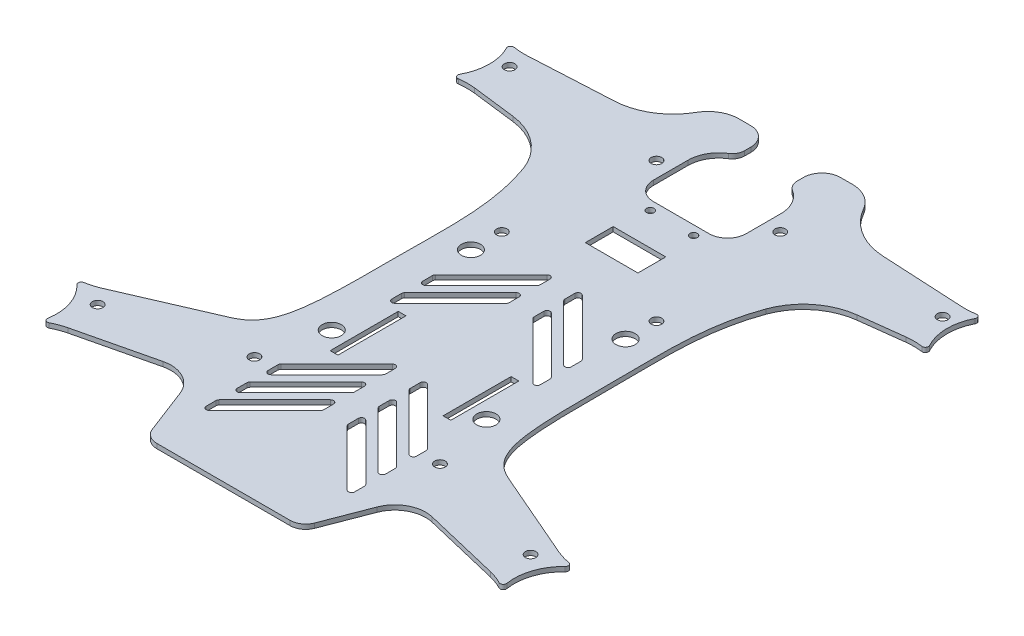
SolidWorks part; units mm, degrees
ref_plane "Front Plane" through (0, 0, 0) normal (0, 0, 1) x (1, 0, 0)
ref_plane "Top Plane" through (0, 0, 0) normal (0, 1, 0) x (1, 0, 0)
ref_plane "Right Plane" through (0, 0, 0) normal (1, 0, 0) x (0, 0, -1)
sketch "Sketch1" plane through (0, 0, 0) normal (0, 1, 0) x (1, 0, 0)
  line L1 (0, 0) -> (0, -50000) construction
  line L12 (-31.8558, -72.1926) -> (-26.2334, -86.7965)
  line L13 (-21.5672, -90) -> (21.5672, -90)
  line L14 (26.2334, -86.7965) -> (31.8558, -72.1926)
  line L15 (43.5115, -66.0592) -> (68.2422, -71.9668)
  line L16 (73.7738, -55.3719) -> (45, -42.8995)
  line L17 (55.6344, 59.1911) -> (69.7041, 60.9187)
  line L18 (70.267, 78.432) -> (43.3651, 79.8419)
  line L19 (18.3249, 95) -> (-18.3249, 95)
  line L20 (-43.3651, 79.8419) -> (-70.267, 78.432)
  line L21 (-69.7041, 60.9187) -> (-55.6344, 59.1911)
  line L22 (-45, -42.8995) -> (-73.7738, -55.3719)
  line L23 (-68.2422, -71.9668) -> (-43.5115, -66.0592)
  line L24 (-31.8558, -72.1926) -> (-26.2334, -86.7965)
  line L25 (-21.5672, -90) -> (21.5672, -90)
  line L26 (26.2334, -86.7965) -> (31.8558, -72.1926)
  line L27 (43.5115, -66.0592) -> (68.2422, -71.9668)
  line L28 (73.7738, -55.3719) -> (45, -42.8995)
  line L29 (55.6344, 59.1911) -> (69.7041, 60.9187)
  line L30 (70.267, 78.432) -> (43.3651, 79.8419)
  line L31 (18.3249, 95) -> (-18.3249, 95)
  line L32 (-43.3651, 79.8419) -> (-70.267, 78.432)
  line L33 (-69.7041, 60.9187) -> (-55.6344, 59.1911)
  line L34 (-45, -42.8995) -> (-73.7738, -55.3719)
  line L35 (-68.2422, -71.9668) -> (-43.5115, -66.0592)
  arc A2 (-18.3249, 95) -> (-27.0205, 89.9382) centre (-18.3249, 85) ccw construction
  arc A3 (-18.3249, 95) -> (-27.0205, 89.9382) centre (-18.3249, 85) ccw
  arc A22 (21.5672, -90) -> (26.2334, -86.7965) centre (21.5672, -85) ccw
  arc A23 (21.5672, -90) -> (26.2334, -86.7965) centre (21.5672, -85) ccw
  arc A24 (43.5115, -66.0592) -> (31.8558, -72.1926) centre (41.1881, -75.7855) ccw
  arc A25 (79.1275, -78.8198) -> (68.2422, -71.9668) centre (63.5953, -91.4195) ccw
  arc A26 (79.1275, -78.8198) -> (86.5939, -56.4207) centre (90, -70) ccw
  arc A27 (73.7738, -55.3719) -> (86.5939, -56.4207) centre (81.728, -37.0216) ccw
  arc A28 (55.6344, 59.1911) -> (39.2597, 46.1303) centre (58.0718, 39.3402) ccw
  arc A29 (82.6465, 58.0867) -> (69.7041, 60.9187) centre (72.1415, 41.0677) ccw
  arc A30 (82.6465, 58.0867) -> (82.3057, 81.696) centre (90, 70) ccw
  arc A31 (70.267, 78.432) -> (82.3057, 81.696) centre (71.3137, 98.4046) ccw
  arc A32 (27.0205, 89.9382) -> (43.3651, 79.8419) centre (44.4119, 99.8145) ccw
  arc A33 (27.0205, 89.9382) -> (18.3249, 95) centre (18.3249, 85) ccw
  arc A34 (-18.3249, 95) -> (-27.0205, 89.9382) centre (-18.3249, 85) ccw
  arc A35 (-43.3651, 79.8419) -> (-27.0205, 89.9382) centre (-44.4119, 99.8145) ccw
  arc A36 (-82.3057, 81.696) -> (-70.267, 78.432) centre (-71.3137, 98.4046) ccw
  arc A37 (-82.3057, 81.696) -> (-82.6465, 58.0867) centre (-90, 70) ccw
  arc A38 (-69.7041, 60.9187) -> (-82.6465, 58.0867) centre (-72.1415, 41.0677) ccw
  arc A39 (-39.2597, 46.1303) -> (-55.6344, 59.1911) centre (-58.0718, 39.3402) ccw
  arc A40 (-86.5939, -56.4207) -> (-73.7738, -55.3719) centre (-81.728, -37.0216) ccw
  arc A41 (-86.5939, -56.4207) -> (-79.1275, -78.8198) centre (-90, -70) ccw
  arc A42 (-68.2422, -71.9668) -> (-79.1275, -78.8198) centre (-63.5953, -91.4195) ccw
  arc A43 (-31.8558, -72.1926) -> (-43.5115, -66.0592) centre (-41.1881, -75.7855) ccw
  arc A44 (-26.2334, -86.7965) -> (-21.5672, -90) centre (-21.5672, -85) ccw
  arc A45 (-26.2334, -86.7965) -> (-21.5672, -90) centre (-21.5672, -85) ccw
  arc A46 (43.5115, -66.0592) -> (31.8558, -72.1926) centre (41.1881, -75.7855) ccw
  arc A47 (68.2422, -71.9668) -> (74.7411, -74.8131) centre (63.5953, -91.4195) cw
  arc A49 (74.7411, -74.8131) -> (80.6807, -56.9942) centre (90, -70) cw
  arc A50 (55.6344, 59.1911) -> (39.2597, 46.1303) centre (58.0718, 39.3402) ccw
  arc A51 (80.6807, -56.9942) -> (73.7738, -55.3719) centre (81.728, -37.0216) cw
  arc A53 (69.7041, 60.9187) -> (77.1837, 60.4217) centre (72.1415, 41.0677) cw
  arc A54 (27.0205, 89.9382) -> (43.3651, 79.8419) centre (44.4119, 99.8145) ccw
  arc A55 (27.0205, 89.9382) -> (18.3249, 95) centre (18.3249, 85) ccw
  arc A57 (-43.3651, 79.8419) -> (-27.0205, 89.9382) centre (-44.4119, 99.8145) ccw
  arc A58 (-76.9126, 79.2043) -> (-70.267, 78.432) centre (-71.3137, 98.4046) ccw
  arc A60 (-69.7041, 60.9187) -> (-77.1837, 60.4217) centre (-72.1415, 41.0677) ccw
  arc A61 (-39.2597, 46.1303) -> (-55.6344, 59.1911) centre (-58.0718, 39.3402) ccw
  arc A62 (-80.6807, -56.9942) -> (-73.7738, -55.3719) centre (-81.728, -37.0216) ccw
  arc A64 (-68.2422, -71.9668) -> (-74.7411, -74.8131) centre (-63.5953, -91.4195) ccw
  arc A65 (-31.8558, -72.1926) -> (-43.5115, -66.0592) centre (-41.1881, -75.7855) ccw
  arc A131 (-77.1837, 60.4217) -> (-76.9126, 79.2043) centre (-90, 70) ccw
  arc A133 (-82.3057, 81.696) -> (-70.267, 78.432) centre (-71.3137, 98.4046) ccw construction
  arc A134 (-74.7411, -74.8131) -> (-80.6807, -56.9942) centre (-90, -70) ccw
  arc A135 (-68.2422, -71.9668) -> (-79.1275, -78.8198) centre (-63.5953, -91.4195) ccw construction
  arc A136 (77.1837, 60.4217) -> (76.9126, 79.2043) centre (90, 70) cw
  arc A137 (76.9126, 79.2043) -> (70.267, 78.432) centre (71.3137, 98.4046) cw
  spline S2 degree 3 poles (1694.5385, -1156.2791) (84.776, 273.5101) (33.8756, -163.1642) (35.6323, 88.6713) (8.3125, 229.0595) (2032.4445, 110.5715) knots -2.898173 -2.898173 -2.898173 -2.898173 0.549242 0.649242 2.552813 2.552813 2.552813 2.552813 only from (45, -42.8995) to (39.2597, 46.1303)
  spline S3 degree 3 poles (-2032.3973, 110.5742) (-8.3129, 229.0574) (-35.6323, 88.6706) (-33.8756, -163.1654) (-84.7767, 273.5164) (-1694.5744, -1156.311) knots -1.552799 -1.552799 -1.552799 -1.552799 0.350758 0.450758 3.898198 3.898198 3.898198 3.898198 only from (-39.2597, 46.1303) to (-45, -42.8995)
  spline S4 degree 3 poles (45, -42.8995) (36.3436, -39.1473) (34.8096, -29.2686) (35.1069, 13.3566) (34.256, 32.2676) (39.2597, 46.1303) knots 0 0 0 0 0.549242 0.649242 0.922623 0.922623 0.922623 0.922623
  spline S5 degree 3 poles (-39.2597, 46.1303) (-34.256, 32.2676) (-35.1069, 13.3566) (-34.8096, -29.2686) (-36.3436, -39.1473) (-45, -42.8995) knots 0.077377 0.077377 0.077377 0.077377 0.350758 0.450758 1 1 1 1
  dimension "D4" = 32
  dimension "D1" = 0
extrude "Boss-Extrude1" add sketch "Sketch1" along normal blind 1.5
sketch "Sketch2" plane through (0, 1.5, 0) normal (0, 1, 0) x (1, 0, 0)
  circle A0 centre (-70, 72.5) radius 1.7 construction
  circle A1 centre (-70, 72.5) radius 1.7
  circle A2 centre (-20, 70) radius 1.7 construction
  circle A3 centre (-20, 70) radius 1.7
  circle A4 centre (20, 70) radius 1.7 construction
  circle A5 centre (20, 70) radius 1.7
  circle A6 centre (70, 72.5) radius 1.7 construction
  circle A7 centre (70, 72.5) radius 1.7
  circle A8 centre (30, -50) radius 1.7 construction
  circle A9 centre (30, -50) radius 1.7
  circle A10 centre (70, -60.6981) radius 1.7 construction
  circle A11 centre (70, -60.6981) radius 1.7
  circle A12 centre (-30, -50) radius 1.7 construction
  circle A13 centre (-30, -50) radius 1.7
  circle A14 centre (-70, -60.6981) radius 1.7 construction
  circle A15 centre (-70, -60.6981) radius 1.7
  circle A16 centre (-25, 25) radius 1.7 construction
  circle A17 centre (-25, 25) radius 1.7
  circle A18 centre (25, 25) radius 1.7 construction
  circle A19 centre (25, 25) radius 1.7
extrude "Cut-Extrude1" cut sketch "Sketch2" against normal through all
sketch "Sketch3" plane through (0, 1.5, 0) normal (0, 1, 0) x (1, 0, 0)
  line L0 (0, 0) -> (0, -50000) construction
  line L1 (-8.5, 83) -> (-15, 83)
  line L2 (15, 83) -> (8.5, 83)
  line L3 (15, 83) -> (15, 58)
  line L4 (15, 58) -> (-15, 58)
  line L5 (-15, 83) -> (-15, 58)
  line L6 (15, 83) -> (-15, 58) construction
  line L7 (15, 58) -> (-15, 83) construction
  line L8 (-8.5, 83) -> (-8.5, 95)
  line L9 (18.3249, 95) -> (-18.3249, 95) construction
  line L10 (-8.5, 95) -> (8.5, 95)
  line L11 (8.5, 95) -> (8.5, 83)
  circle A0 centre (-7, 55) radius 1.2
  circle A1 centre (7, 55) radius 1.2
  point P3 (0, 70.5)
  dimension "D4" = 17
  dimension "D5" = 14
  dimension "D6" = 2.4
  dimension "D1" = 25
  dimension "D2" = 58
  dimension "D3" = 30
  dimension "D7" = 3
extrude "Cut-Extrude2" cut sketch "Sketch3" against normal through all
fillet "Fillet1" radius 6 2 edges at (8.5, 0.75, -95) (-8.5, 0.75, -95)
fillet "Fillet2" radius 4 2 edges at (8.5, 0.75, -83) (-8.5, 0.75, -83)
fillet "Fillet3" radius 10 2 edges at (15, 0.75, -83) (-15, 0.75, -83)
fillet "Fillet4" radius 6 2 edges at (15, 0.75, -58) (-15, 0.75, -58)
sketch "Sketch4" plane through (0, 1.5, 0) normal (0, 1, 0) x (1, 0, 0)
  line L0 (0, 0) -> (0, -50000) construction
  circle A0 centre (-25, 15) radius 3.1
  circle A1 centre (25, 15) radius 3.1
  circle A2 centre (-25, -30) radius 3.1
  circle A3 centre (25, -30) radius 3.1
  dimension "D1" = 6.2
  dimension "D2" = 50
  dimension "D3" = 45
  dimension "D4" = 15
extrude "Cut-Extrude3" cut sketch "Sketch4" against normal through all
sketch "Sketch5" plane through (0, 1.5, 0) normal (0, 1, 0) x (1, 0, 0)
  line L1 (8.5, 44.5) -> (-8.5, 44.5)
  line L2 (8.5, 44.5) -> (8.5, 35.5)
  line L3 (8.5, 35.5) -> (-8.5, 35.5)
  line L4 (-8.5, 44.5) -> (-8.5, 35.5)
  line L5 (8.5, 44.5) -> (-8.5, 35.5) construction
  line L6 (8.5, 35.5) -> (-8.5, 44.5) construction
  point P0 (0, 40)
  dimension "D1" = 17
  dimension "D2" = 9
  dimension "D3" = 40
extrude "Cut-Extrude4" cut sketch "Sketch5" against normal through all
sketch "Sketch6" plane through (0, 1.5, 0) normal (0, 1, 0) x (1, 0, 0)
  line L0 (-24, -8) -> (-4, 12) [skipped]
  line L1 (-4, 22) -> (-4, 16)
  line L2 (-4, 16) -> (-24, -4)
  line L3 (-24, -4) -> (-24, 2)
  line L4 (-24, 2) -> (-4, 22)
  line L5 (-4, 12) -> (-4, 6)
  line L6 (-24, -8) -> (-4, 12)
  line L7 (-24, -14) -> (-24, -8)
  line L8 (-4, 6) -> (-24, -14)
  line L9 (-24, -48) -> (-4, -28)
  line L10 (-24, -54) -> (-24, -48)
  line L11 (-4, -34) -> (-24, -54)
  line L12 (-4, -28) -> (-4, -34)
  line L13 (-24, -14) -> (-24, -8) [skipped]
  line L14 (-4, 6) -> (-24, -14) [skipped]
  line L15 (-4, 12) -> (-4, 6) [skipped]
  line L16 (-24, -18) -> (-4, 2) [skipped]
  line L17 (-24, -24) -> (-24, -18) [skipped]
  line L18 (-4, -4) -> (-24, -24) [skipped]
  line L19 (-4, 2) -> (-4, -4) [skipped]
  line L20 (-24, -28) -> (-4, -8) [skipped]
  line L21 (-24, -34) -> (-24, -28) [skipped]
  line L22 (-4, -14) -> (-24, -34) [skipped]
  line L23 (-4, -8) -> (-4, -14) [skipped]
  line L24 (-24, -38) -> (-4, -18) [skipped]
  line L25 (-24, -44) -> (-24, -38) [skipped]
  line L26 (-4, -24) -> (-24, -44) [skipped]
  line L27 (-4, -18) -> (-4, -24) [skipped]
  line L32 (-24, -58) -> (-4, -38)
  line L33 (-24, -64) -> (-24, -58)
  line L34 (-4, -44) -> (-24, -64)
  line L35 (-4, -38) -> (-4, -44)
  line L36 (-24, -68) -> (-4, -48)
  line L37 (-24, -74) -> (-24, -68)
  line L38 (-4, -54) -> (-24, -74)
  line L39 (-4, -48) -> (-4, -54)
  line L95 (-24, -48) -> (-4, -28) [skipped]
  line L96 (-4, -28) -> (-4, -34) [skipped]
  line L97 (-4, -34) -> (-24, -54) [skipped]
  line L98 (-24, -54) -> (-24, -48) [skipped]
  line L99 (-24, -18) -> (-4, 2) [skipped]
  line L100 (-24, -24) -> (-24, -18) [skipped]
  line L101 (-4, -4) -> (-24, -24) [skipped]
  line L102 (-4, 2) -> (-4, -4) [skipped]
  dimension "D1" = 20
  dimension "D2" = 8
  dimension "D3" = 22
  dimension "D4" = 20
  dimension "D5" = 6
  dimension "D6" = 3
  dimension "D7" = 2
  dimension "D8" = 4
extrude "Cut-Extrude5" cut sketch "Sketch6" against normal through all
fillet "Fillet5" radius 1 20 edges at (-24, 0.75, 14) (-24, 0.75, 8) (-4, 0.75, -6) (-4, 0.75, -12) (-4, 0.75, -16) (-4, 0.75, -22) (-24, 0.75, 4) (-24, 0.75, -2) (-4, 0.75, 38) (-4, 0.75, 44) (-4, 0.75, 48) (-4, 0.75, 54) (-24, 0.75, 74) (-24, 0.75, 68) (-24, 0.75, 64) (-24, 0.75, 58) (-4, 0.75, 28) (-4, 0.75, 34) (-24, 0.75, 54) (-24, 0.75, 48)
mirror "Mirror1" about plane through (0, 0, 0) normal (1, 0, 0) of "Fillet5", "Cut-Extrude5"
fillet "Fillet6" radius 1 8 edges at (77.1837, 0.75, -60.4217) (76.9126, 0.75, -79.2043) (74.7411, 0.75, 74.8131) (80.6807, 0.75, 56.9942) (-74.7411, 0.75, 74.8131) (-80.6807, 0.75, 56.9942) (-77.1837, 0.75, -60.4217) (-76.9126, 0.75, -79.2043)
sketch "Sketch7" plane through (0, 1.5, 0) normal (0, 1, 0) x (1, 0, 0)
  line L0 (0, 0) -> (0, -50000) construction
  line L1 (17, -14) -> (17, -36)
  line L2 (-19.5, -14) -> (-17, -14)
  line L3 (-19.5, -14) -> (-19.5, -36)
  line L4 (-19.5, -36) -> (-17, -36)
  line L5 (-17, -14) -> (-17, -36)
  line L6 (19.5, -36) -> (17, -36)
  line L7 (19.5, -14) -> (19.5, -36)
  line L8 (19.5, -14) -> (17, -14)
  point P7 (-18.25, -14)
  dimension "D1" = 2.5
  dimension "D2" = 14
  dimension "D3" = 22
  dimension "D4" = 17
extrude "Cut-Extrude6" cut sketch "Sketch7" against normal through all
